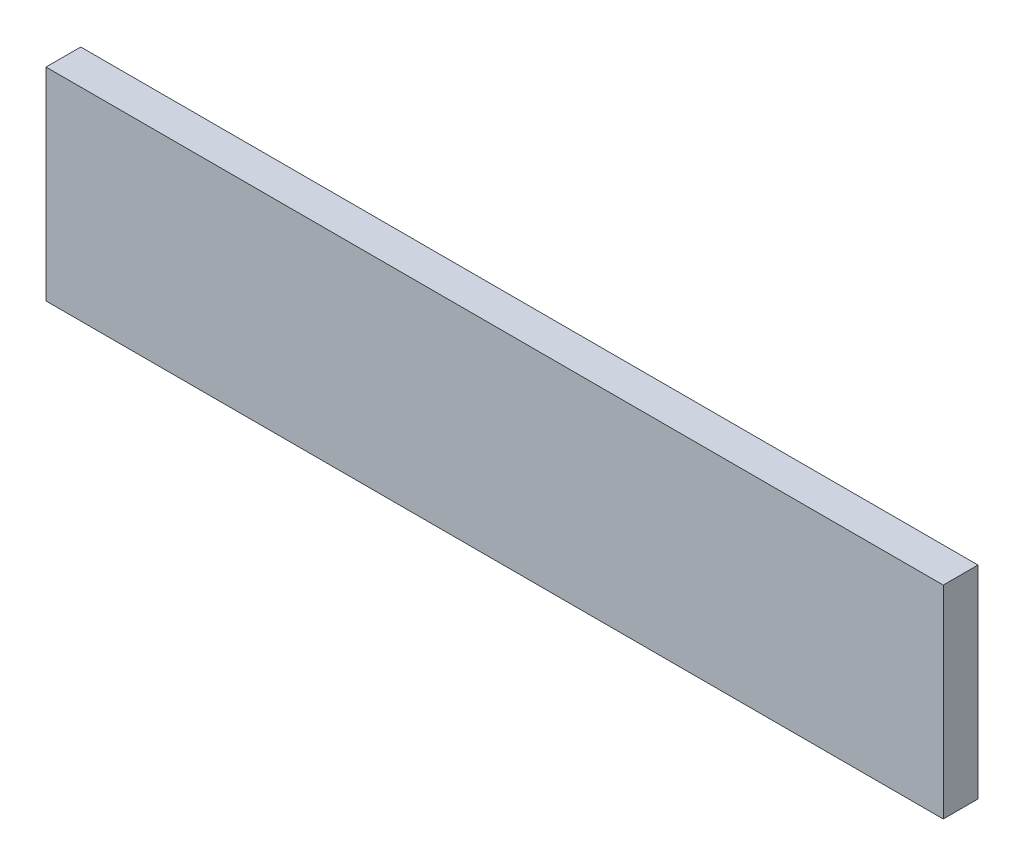
SolidWorks part; units mm, degrees
ref_plane "前视基准面" through (0, 0, 0) normal (0, 0, 1) x (1, 0, 0)
ref_plane "上视基准面" through (0, 0, 0) normal (0, 1, 0) x (1, 0, 0)
ref_plane "右视基准面" through (0, 0, 0) normal (1, 0, 0) x (0, 0, -1)
sketch "草图1" plane through (0, 0, 0) normal (0, 0, 1) x (1, 0, 0)
  line L0 (-853.9894, 35) -> (49146.0106, 35) construction
  line L1 (0, 0) -> (310, 0)
  line L2 (0, 0) -> (0, 70)
  line L3 (0, 70) -> (310, 70)
  line L4 (310, 0) -> (310, 70)
  dimension "D1" = 310
  dimension "D2" = 70
  dimension "D3" = 35
extrude "凸台-拉伸1" add sketch "草图1" along normal blind 12
